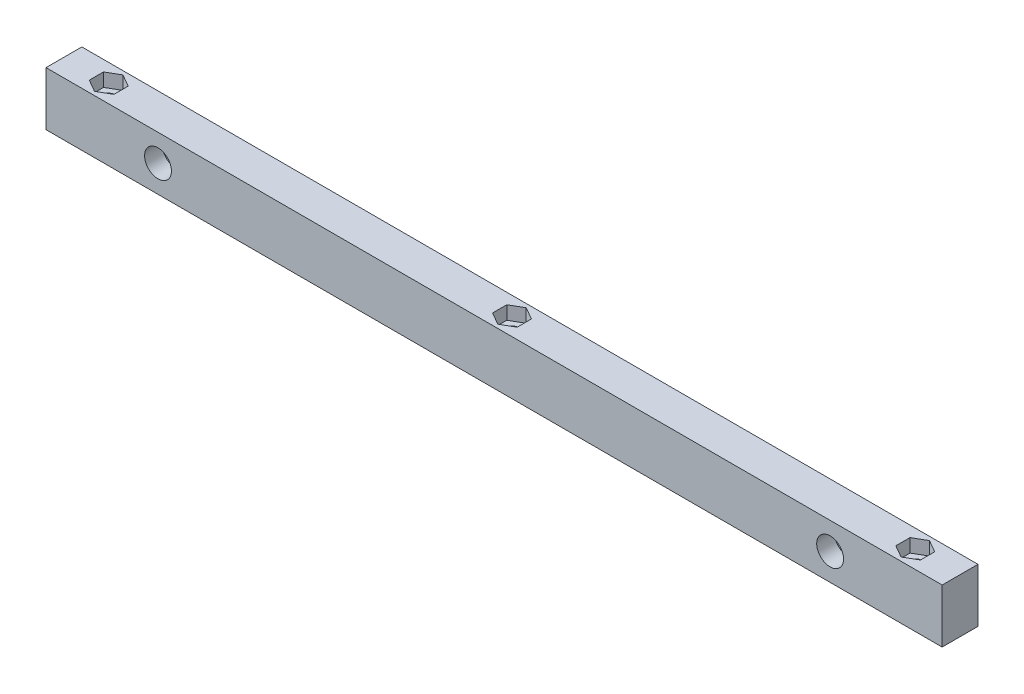
SolidWorks part; units mm, degrees
material "ABS"
ref_plane "Front" through (0, 0, 0) normal (0, 0, 1) x (1, 0, 0)
ref_plane "Top" through (0, 0, 0) normal (0, 1, 0) x (1, 0, 0)
ref_plane "Right" through (0, 0, 0) normal (1, 0, 0) x (0, 0, -1)
sketch "Esquisse1" plane through (0, 0, 0) normal (0, 1, 0) x (1, 0, 0)
  line L1 (-100, 8) -> (100, 8)
  line L2 (-100, 8) -> (-100, 0)
  line L3 (-100, 0) -> (100, 0)
  line L4 (100, 8) -> (100, 0)
  dimension "D1" = 8
  dimension "D2" = 200
extrude "Boss.-Extru.1" add sketch "Esquisse1" along normal blind 12
sketch "Esquisse2" plane through (0, 12, 0) normal (0, 1, 0) x (1, 0, 0)
  line L0 (-100, 8) -> (-100, 0) construction
  circle A0 centre (-90, 4) radius 1.5
  circle A1 centre (0, 4) radius 1.5
  circle A2 centre (90, 4) radius 1.5
  point P9 (-100, 4)
  dimension "D1" = 3
  dimension "D2" = 3
  dimension "D3" = 90
extrude "Enlèv. mat.-Extru.1" cut sketch "Esquisse2" against normal through all
sketch "Esquisse3" plane through (0, 0, 0) normal (0, 0, 1) x (1, 0, 0)
  line L0 (-100, 12) -> (-100, 0) construction
  line L1 (0, -50) -> (0, 50) construction
  circle A0 centre (-75, 6) radius 1.5
  circle A1 centre (75, 6) radius 1.5
  point P4 (-100, 6)
  dimension "D1" = 3
  dimension "D2" = 150
extrude "Enlèv. mat.-Extru.2" cut sketch "Esquisse3" against normal through all
sketch "Esquisse4" plane through (0, 0, 0) normal (0, 0, 1) x (1, 0, 0)
  circle A0 centre (-75, 6) radius 3
  circle A1 centre (75, 6) radius 3
  circle A2 centre (75, 6) radius 1.5 construction
  circle A3 centre (-75, 6) radius 1.5 construction
  dimension "D1" = 6
extrude "Enlèv. mat.-Extru.3" cut sketch "Esquisse4" against normal blind 4
sketch "Esquisse5" plane through (0, 12, 0) normal (0, 1, 0) x (1, 0, 0)
  line L1 (-87.25, 5.5877) -> (-90, 7.1754)
  line L2 (-90, 7.1754) -> (-92.75, 5.5877)
  line L3 (-92.75, 5.5877) -> (-92.75, 2.4123)
  line L4 (-92.75, 2.4123) -> (-90, 0.8246)
  line L5 (-90, 0.8246) -> (-87.25, 2.4123)
  line L6 (-87.25, 2.4123) -> (-87.25, 5.5877)
  line L7 (2.75, 5.5877) -> (0, 7.1754)
  line L8 (0, 7.1754) -> (-2.75, 5.5877)
  line L9 (-2.75, 5.5877) -> (-2.75, 2.4123)
  line L10 (-2.75, 2.4123) -> (0, 0.8246)
  line L11 (0, 0.8246) -> (2.75, 2.4123)
  line L12 (2.75, 2.4123) -> (2.75, 5.5877)
  line L13 (92.75, 5.5877) -> (90, 7.1754)
  line L14 (90, 7.1754) -> (87.25, 5.5877)
  line L15 (87.25, 5.5877) -> (87.25, 2.4123)
  line L16 (87.25, 2.4123) -> (90, 0.8246)
  line L17 (90, 0.8246) -> (92.75, 2.4123)
  line L18 (92.75, 2.4123) -> (92.75, 5.5877)
  circle A0 centre (-90, 4) radius 2.75 construction
  circle A1 centre (0, 4) radius 2.75 construction
  circle A2 centre (90, 4) radius 2.75 construction
  dimension "D1" = 5.5
extrude "Enlèv. mat.-Extru.4" cut sketch "Esquisse5" against normal blind 3
sketch "Esquisse6" plane through (0, 0, -8) normal (0, 0, -1) x (-1, 0, 0)
  line L4 (-100, 0) -> (100, 0)
  line L5 (100, 0) -> (100, 12)
  line L6 (100, 12) -> (-100, 12)
  line L7 (-100, 12) -> (-100, 0)
  line L8 (-100, 0) -> (100, 0)
  line L9 (100, 0) -> (100, 12)
  line L10 (100, 12) -> (-100, 12)
  line L11 (-100, 12) -> (-100, 0)
  dimension "D1" = 0
extrude "Boss.-Extru.2" [suppressed] add sketch "Esquisse6" against normal blind 0.2
